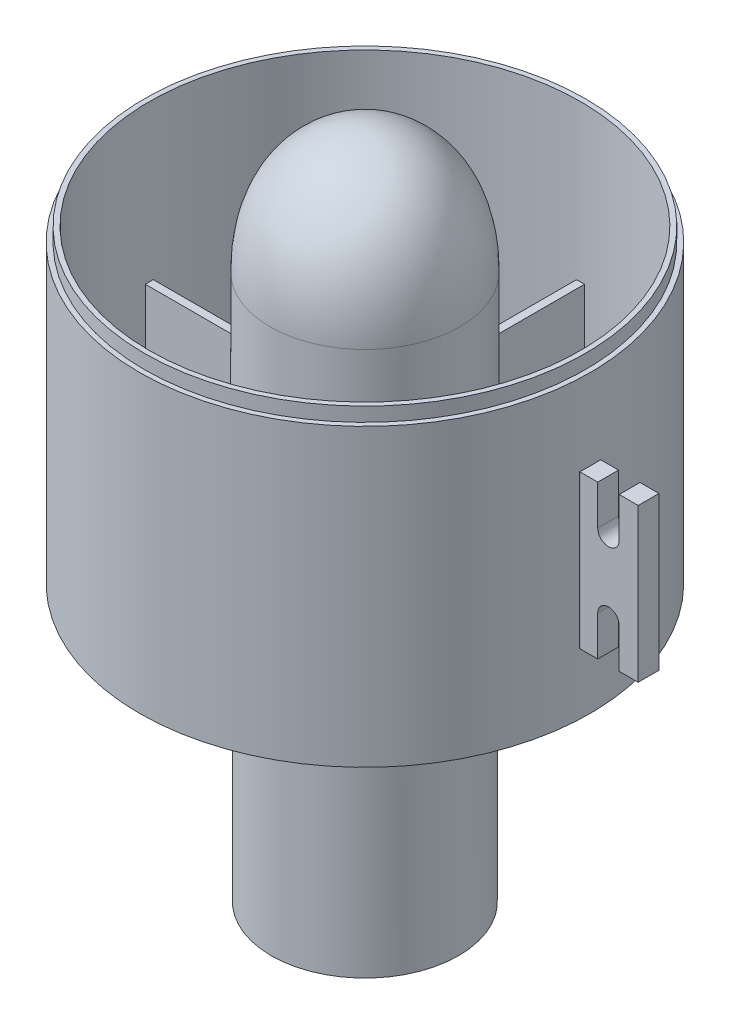
SolidWorks part; units mm, degrees
ref_plane "Front Plane" through (0, 0, 0) normal (0, 0, 1) x (1, 0, 0)
ref_plane "Top Plane" through (0, 0, 0) normal (0, 1, 0) x (1, 0, 0)
ref_plane "Right Plane" through (0, 0, 0) normal (1, 0, 0) x (0, 0, -1)
sketch "Sketch1" plane through (0, 0, 0) normal (0, 1, 0) x (1, 0, 0)
  circle A0 centre (0, 0) radius 36.8
  circle A2 centre (0, 0) radius 35.2
  dimension "D1" = 73.6
  dimension "D2" = 1.6
extrude "Boss-Extrude1" add sketch "Sketch1" along normal blind 50.5
sketch "Sketch2" plane through (0, 0, 0) normal (0, -1, 0) x (1, 0, 0)
  line L0 (-36.8, 0) -> (-16, 0) construction
  line L1 (15.9868, 0.65) -> (35.194, 0.65)
  line L2 (15.9868, -0.65) -> (35.194, -0.65)
  line L3 (11.764, -10.8447) -> (25.3455, -24.4263)
  line L4 (10.8447, -11.764) -> (24.4263, -25.3455)
  line L5 (0.65, -15.9868) -> (0.65, -35.194)
  line L6 (-0.65, -15.9868) -> (-0.65, -35.194)
  line L7 (-10.8447, -11.764) -> (-24.4263, -25.3455)
  line L8 (-11.764, -10.8447) -> (-25.3455, -24.4263)
  line L9 (-15.9868, -0.65) -> (-35.194, -0.65)
  line L10 (-15.9868, 0.65) -> (-35.194, 0.65)
  line L11 (-11.764, 10.8447) -> (-25.3455, 24.4263)
  line L12 (-10.8447, 11.764) -> (-24.4263, 25.3455)
  line L13 (-0.65, 15.9868) -> (-0.65, 35.194)
  line L14 (0.65, 15.9868) -> (0.65, 35.194)
  line L15 (10.8447, 11.764) -> (24.4263, 25.3455)
  line L16 (11.764, 10.8447) -> (25.3455, 24.4263)
  line L17 (-15, 0) -> (15.7396, 0) construction
  circle A0 centre (0, 0) radius 36.8 construction
  arc A1 (-15.9868, -0.65) -> (-11.764, -10.8447) centre (0, 0) ccw
  circle A2 centre (0, 0) radius 15
  circle A3 centre (0, 0) radius 35.2 construction
  circle A4 centre (0, 0) radius 16 construction
  arc A5 (-11.764, 10.8447) -> (-15.9868, 0.65) centre (0, 0) ccw
  arc A6 (-0.65, 15.9868) -> (-10.8447, 11.764) centre (0, 0) ccw
  arc A7 (10.8447, 11.764) -> (0.65, 15.9868) centre (0, 0) ccw
  arc A8 (15.9868, 0.65) -> (11.764, 10.8447) centre (0, 0) ccw
  arc A9 (11.764, -10.8447) -> (15.9868, -0.65) centre (0, 0) ccw
  arc A10 (0.65, -15.9868) -> (10.8447, -11.764) centre (0, 0) ccw
  arc A11 (-10.8447, -11.764) -> (-0.65, -15.9868) centre (0, 0) ccw
  arc A12 (-35.194, 0.65) -> (-35.194, -0.65) centre (0, 0) ccw
  arc A13 (-24.4263, 25.3455) -> (-25.3455, 24.4263) centre (0, 0) ccw
  arc A14 (0.65, 35.194) -> (-0.65, 35.194) centre (0, 0) ccw
  arc A15 (25.3455, 24.4263) -> (24.4263, 25.3455) centre (0, 0) ccw
  arc A16 (35.194, -0.65) -> (35.194, 0.65) centre (0, 0) ccw
  arc A17 (24.4263, -25.3455) -> (25.3455, -24.4263) centre (0, 0) ccw
  arc A18 (-0.65, -35.194) -> (0.65, -35.194) centre (0, 0) ccw
  arc A19 (-25.3455, -24.4263) -> (-24.4263, -25.3455) centre (0, 0) ccw
  point P46 (0, 0)
  dimension "D1" = 32
  dimension "D3" = 1.3
  dimension "D2" = 1
  dimension "D4" = 8
extrude "Boss-Extrude2" add sketch "Sketch2" against normal blind 25
ref_axis "Axis1" through (0, 25, 0) along (0, -1, 0)
sketch "Sketch3" plane through (0, 0, 0) normal (0, 0, 1) x (0, -1, 0)
  line L0 (0, 36.8008) -> (-50.5, 36.8008) construction
  line L1 (0, -36.8) -> (0, 36.8) construction
  line L2 (-50.5, 36.8) -> (-50.5, -36.8) construction
  line L3 (-35, 41.45) -> (-10, 41.45) construction
  line L4 (-35, 36.8008) -> (-10, 36.8008)
  line L5 (-35, 36.8008) -> (-35, 39.7)
  line L6 (-35, 46.3008) -> (-10, 46.3008)
  line L7 (-10, 36.8008) -> (-10, 39.7)
  line L8 (-28.5, 43.2) -> (-35, 43.2)
  line L9 (-28.5, 39.7) -> (-35, 39.7)
  line L10 (-35, 43.2) -> (-35, 46.3008)
  line L11 (-22.5, 46.3008) -> (-22.5, 36.8008) construction
  line L12 (-16.5, 39.7) -> (-10, 39.7)
  line L13 (-16.5, 43.2) -> (-10, 43.2)
  line L14 (-10, 43.2) -> (-10, 46.3008)
  line L15 (-50.5, 0) -> (0, 0) construction
  line L16 (-16.5, -39.7) -> (-10, -39.7)
  line L17 (-16.5, -43.2) -> (-10, -43.2)
  line L18 (-35, -43.2) -> (-35, -46.3008)
  line L19 (-28.5, -43.2) -> (-35, -43.2)
  line L20 (-28.5, -39.7) -> (-35, -39.7)
  line L21 (-35, -36.8008) -> (-35, -39.7)
  line L22 (-35, -36.8008) -> (-10, -36.8008)
  line L23 (-10, -36.8008) -> (-10, -39.7)
  line L24 (-10, -43.2) -> (-10, -46.3008)
  line L25 (-35, -46.3008) -> (-10, -46.3008)
  arc A0 (-28.5, 39.7) -> (-28.5, 43.2) centre (-28.5, 41.45) ccw
  arc A1 (-16.5, 39.7) -> (-16.5, 43.2) centre (-16.5, 41.45) cw
  arc A2 (-28.5, -39.7) -> (-28.5, -43.2) centre (-28.5, -41.45) cw
  arc A3 (-16.5, -39.7) -> (-16.5, -43.2) centre (-16.5, -41.45) ccw
  dimension "D4" = 3.5
  dimension "D1" = 10
  dimension "D2" = 25
  dimension "D3" = 9.5
  dimension "D5" = 6.5
extrude "Boss-Extrude3" add sketch "Sketch3" along normal blind 1.7 and the other way blind 1.7 separate body
sketch "Sketch4" plane through (36.8008, 0, 0) normal (-1, 0, 0) x (0, 0, 1)
  line L1 (-1.7, 35) -> (1.7, 35)
  line L2 (-1.7, 35) -> (-1.7, 10)
  line L3 (-1.7, 10) -> (1.7, 10)
  line L4 (1.7, 35) -> (1.7, 10)
extrude "Boss-Extrude4" add sketch "Sketch4" along normal up to surface (0.0401 mm away)
sketch "Sketch5" plane through (0, 50.5, 0) normal (0, 1, 0) x (1, 0, 0)
  circle A0 centre (0, 0) radius 36.8 construction
  circle A1 centre (0, 0) radius 36.8
  circle A2 centre (0, 0) radius 36
  dimension "D1" = 0.8
extrude "Cut-Extrude1" cut sketch "Sketch5" against normal blind 2.3
sketch "Sketch6" plane through (0, 0, 0) normal (0, -1, 0) x (1, 0, 0)
  circle A0 centre (0, 0) radius 15.3
  dimension "D1" = 30.6
extrude "Boss-Extrude5" add sketch "Sketch6" along normal blind 50
chamfer "Chamfer1" distance 5 angle 60 1 edges at (0, -50, -15.3)
sketch "Sketch7" plane through (0, 0, 0) normal (0, 1, 0) x (1, 0, 0)
  circle A0 centre (0, 0) radius 15.5
  dimension "D1" = 31
extrude "Boss-Extrude6" add sketch "Sketch7" along normal blind 44
sketch "Sketch8" plane through (0, 0, 0) normal (0, 0, 1) x (0, -1, 0)
  line L0 (-44, 0) -> (-83.5149, 0) construction
  line L1 (-44, 15.5) -> (-44, -15.5) construction
  line L2 (-64, 19.8889) -> (-64, -13.7445) construction
  line L3 (-64, -8.4837) -> (-64, 8.4837) construction
  line L4 (-55.1765, 15.5) -> (-32.8235, 15.5) construction
  line L5 (-44, 15.5) -> (-44, 0)
  line L6 (-64, 0) -> (-44, 0)
  spline S0 degree 3 poles (-44, 15.5) (-57.9706, 15.5) (-64, 7.0697) (-64, 0) knots 0 0 0 0 1 1 1 1
  dimension "D1" = 20
revolve "Revolve2" add sketch "Sketch8" angle 360 about axis through (0, 25, 0) along (0, -1, 0)
